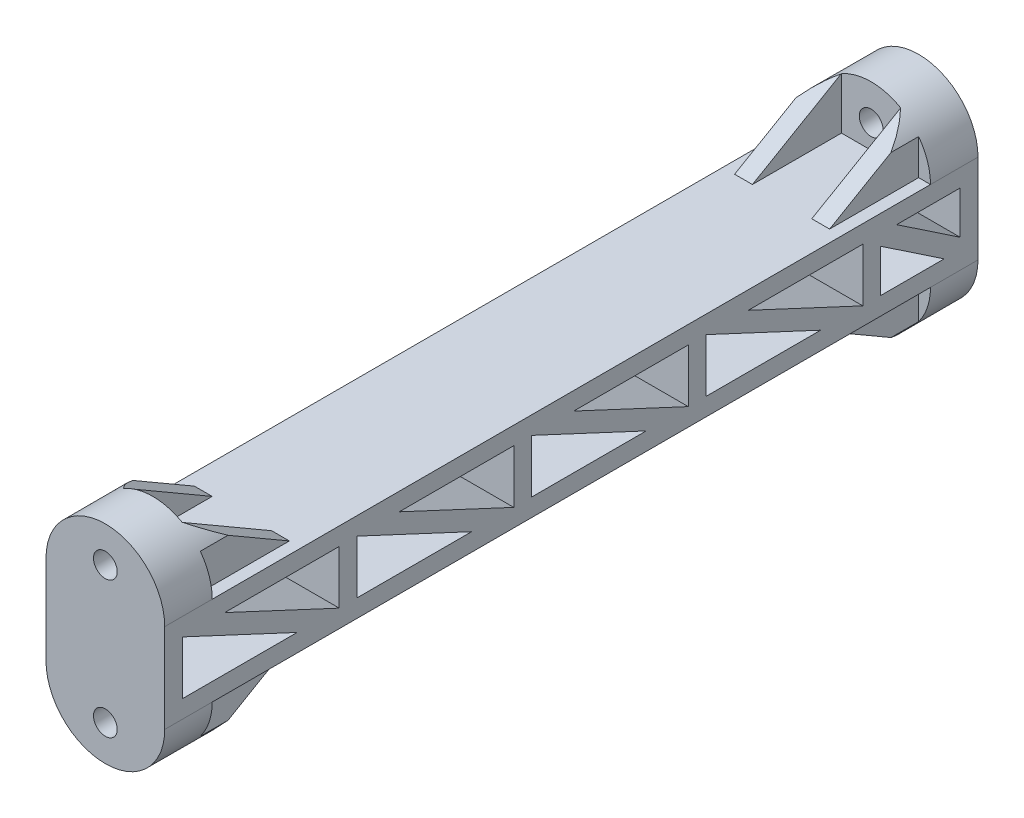
SolidWorks part; units mm, degrees
ref_plane "Front Plane" through (0, 0, 0) normal (0, 0, 1) x (1, 0, 0)
ref_plane "Top Plane" through (0, 0, 0) normal (0, 1, 0) x (1, 0, 0)
ref_plane "Right Plane" through (0, 0, 0) normal (1, 0, 0) x (0, 0, -1)
sketch "Sketch1" plane through (0, 0, 0) normal (0, 0, 1) x (1, 0, 0)
  line L0 (-10, -15) -> (10, -15) construction
  line L1 (10, 0) -> (-10, 0) construction
  line L2 (-10, -15) -> (10, -15)
  line L3 (10, 0) -> (-10, 0)
  circle A0 centre (0, -19) radius 2 construction
  arc A1 (-10, -15) -> (10, -15) centre (0, -15) ccw construction
  arc A2 (10, 0) -> (-10, 0) centre (0, 0) ccw construction
  circle A3 centre (0, 4) radius 2 construction
  circle A4 centre (0, -19) radius 2
  arc A5 (-10, -15) -> (10, -15) centre (0, -15) ccw
  arc A6 (10, 0) -> (-10, 0) centre (0, 0) ccw
  circle A7 centre (0, 4) radius 2
extrude "Boss-Extrude1" add sketch "Sketch1" against normal blind 8
sketch "Sketch2" plane through (-10, 0, 0) normal (-1, 0, 0) x (0, 0, 1)
  line L8 (67, -15) -> (67, -7.5)
  line L9 (67, -7.5) -> (54, -7.5)
  line L10 (54, -7.5) -> (54, 0)
  line L11 (54, 0) -> (0, 0)
  line L12 (0, 0) -> (-8, 0)
  line L13 (-8, 0) -> (-8, -15)
  line L14 (-8, -15) -> (0, -15)
  line L15 (0, -15) -> (67, -15)
  line L16 (67, -15) -> (67, -7.5)
  line L17 (67, -7.5) -> (54, -7.5)
  line L18 (54, -7.5) -> (54, 0)
  line L19 (54, 0) -> (0, 0)
  line L20 (0, 0) -> (-8, 0)
  line L21 (-8, 0) -> (-8, -15)
  line L22 (-8, -15) -> (0, -15)
  line L23 (0, -15) -> (67, -15)
  line L24 (54, 0) -> (54, -7.5)
  line L25 (54, -7.5) -> (67, -7.5)
  line L26 (67, -7.5) -> (67, -15)
  line L27 (67, -15) -> (121, -15)
  line L28 (121, -15) -> (129, -15)
  line L29 (129, -15) -> (129, 0)
  line L30 (129, 0) -> (121, 0)
  line L31 (121, 0) -> (54, 0)
  line L32 (54, 0) -> (54, -7.5)
  line L33 (54, -7.5) -> (67, -7.5)
  line L34 (67, -7.5) -> (67, -15)
  line L35 (67, -15) -> (121, -15)
  line L36 (121, -15) -> (129, -15)
  line L37 (129, -15) -> (129, 0)
  line L38 (129, 0) -> (121, 0)
  line L39 (121, 0) -> (54, 0)
  line M17 (67, -15) -> (67, -7.5)
  line M18 (67, -7.5) -> (54, -7.5)
  line M19 (54, -7.5) -> (54, 0)
  line M20 (54, 0) -> (0, 0)
  line M21 (0, 0) -> (-8, 0)
  line M22 (-8, 0) -> (-8, -15)
  line M23 (-8, -15) -> (0, -15)
  line M24 (0, -15) -> (67, -15)
  dimension "D1" = 0
  dimension "D2" = 0
extrude "Boss-Extrude2" add sketch "Sketch2" against normal blind 20 contours M24 M17 M18 M19 M20 M21 M22 M23
sketch "Sketch3" plane through (-10, 0, 0) normal (-1, 0, 0) x (0, 0, 1)
  line L8 (54, 0) -> (54, -7.5)
  line L9 (54, -7.5) -> (67, -7.5)
  line L10 (67, -7.5) -> (67, -15)
  line L11 (67, -15) -> (121, -15)
  line L12 (121, -15) -> (129, -15)
  line L13 (129, -15) -> (129, 0)
  line L14 (129, 0) -> (121, 0)
  line L15 (121, 0) -> (54, 0)
  line L16 (54, 0) -> (54, -7.5)
  line L17 (54, -7.5) -> (67, -7.5)
  line L18 (67, -7.5) -> (67, -15)
  line L19 (67, -15) -> (121, -15)
  line L20 (121, -15) -> (129, -15)
  line L21 (129, -15) -> (129, 0)
  line L22 (129, 0) -> (121, 0)
  line L23 (121, 0) -> (54, 0)
  dimension "D1" = 0
extrude "Boss-Extrude3" add sketch "Sketch3" against normal blind 20
sketch "Sketch4" plane through (0, 0, 121) normal (0, 0, -1) x (-1, 0, 0)
  line L1 (-10, 0) -> (10, 0)
  line L2 (-10, 0) -> (10, 0)
  line L3 (10, -15) -> (-10, -15)
  line L4 (10, -15) -> (-10, -15)
  circle A0 centre (0, -19) radius 2 construction
  arc A1 (10, 0) -> (-10, 0) centre (0, 0) ccw
  arc A2 (10, 0) -> (-10, 0) centre (0, 0) ccw
  arc A3 (-10, -15) -> (10, -15) centre (0, -15) ccw
  arc A4 (-10, -15) -> (10, -15) centre (0, -15) ccw
  circle A5 centre (0, 4) radius 2 construction
  circle A6 centre (0, -19) radius 2
  circle A7 centre (0, 4) radius 2
  dimension "D1" = 0
  dimension "D2" = 0
extrude "Boss-Extrude4" add sketch "Sketch4" against normal blind 8
sketch "Sketch6" plane through (10, 0, 0) normal (1, 0, 0) x (0, 0, -1)
  line L0 (0, -3) -> (-121, -3)
  line L1 (-121, -3) -> (-126, -3)
  line L2 (-126, -3) -> (-126, -12)
  line L3 (-126, -12) -> (-121, -12)
  line L4 (-121, -12) -> (0, -12)
  line L5 (0, -12) -> (5, -12)
  line L6 (5, -12) -> (5, -3)
  line L7 (5, -3) -> (0, -3)
  line L8 (0, -15) -> (8, -15)
  line L9 (8, -15) -> (8, 0)
  line L10 (8, 0) -> (0, 0)
  line L11 (0, 0) -> (-121, 0)
  line L12 (-121, 0) -> (-129, 0)
  line L13 (-129, 0) -> (-129, -15)
  line L14 (-129, -15) -> (-121, -15)
  line L15 (-121, -15) -> (0, -15)
  line L16 (0, -15) -> (8, -15)
  line L17 (8, -15) -> (8, 0)
  line L18 (8, 0) -> (0, 0)
  line L19 (0, 0) -> (-121, 0)
  line L20 (-121, 0) -> (-129, 0)
  line L21 (-129, 0) -> (-129, -15)
  line L22 (-129, -15) -> (-121, -15)
  line L23 (-121, -15) -> (0, -15)
  dimension "D1" = 0
  dimension "D2" = 3
extrude "Cut-Extrude1" cut sketch "Sketch6" against normal through all contours L0 L1 L2 L3 L4 L5 L6 L7
sketch "Sketch7" plane through (10, 0, 0) normal (1, 0, 0) x (0, 0, -1)
  line L0 (-126, -3) -> (-106.6994, -12)
  line L1 (-126, -3) -> (-118.9014, -3)
  line L2 (5, -3) -> (-126, -3) construction
  line L3 (-126, -12) -> (5, -12) construction
  line L4 (-99.6008, -12) -> (-106.6994, -12)
  line L5 (-126, -3) -> (-126, -12) construction
  line L6 (-118.9014, -3) -> (-99.6008, -12)
  line L7 (-124.7321, -0.2811) -> (-105.4316, -9.2811) construction
  line L8 (-99.6008, -12) -> (-99.6008, -3)
  line L9 (-96.6008, -12) -> (-96.6008, -3)
  line L10 (5, -3) -> (-126, -3)
  line L11 (-126, -12) -> (5, -12)
  line L12 (-96.6008, -3) -> (-77.3003, -12)
  line L13 (-89.5022, -3) -> (-70.2017, -12)
  line L14 (-95.333, -0.2811) -> (-76.0324, -9.2811) construction
  line L15 (-70.2017, -12) -> (-70.2017, -3)
  line L16 (-67.2017, -12) -> (-67.2017, -3)
  line L17 (-67.2017, -3) -> (-47.9011, -12)
  line L18 (-60.1031, -3) -> (-40.8025, -12)
  line L19 (-65.9338, -0.2811) -> (-46.6332, -9.2811) construction
  line L20 (-40.8025, -12) -> (-40.8025, -3)
  line L21 (-37.8025, -12) -> (-37.8025, -3)
  line L22 (-37.8025, -3) -> (-18.5019, -12)
  line L23 (-30.7039, -3) -> (-11.4033, -12)
  line L24 (-36.5346, -0.2811) -> (-17.2341, -9.2811) construction
  line L25 (-11.4033, -12) -> (-11.4033, -3)
  line L26 (-8.4033, -12) -> (-8.4033, -3)
  line L27 (-8.4033, -3) -> (5, -12)
  line L28 (-8.4033, -4.8068) -> (2.3092, -12)
  line L29 (-5.7126, -3) -> (5, -10.1932)
  line L30 (-9.2395, -4.2453) -> (4.1638, -13.2453) construction
  line L31 (5, -12) -> (5, -3) construction
  line L32 (5, -12) -> (5, -3)
  line L33 (-7.5671, -1.7547) -> (5.8362, -10.7547) construction
  point P39 (6.4204, -9.9124)
  point P41 (4.4741, -13.3294)
  point P42 (4.6457, -12)
  line M3 (-126, -3) -> (5, -3)
  line M4 (5, -3) -> (5, -12)
  line M5 (5, -12) -> (-126, -12)
  dimension "D1" = 65
  dimension "D2" = 3
  dimension "D3" = 3
  dimension "D4" = 65
  dimension "D6" = 3
  dimension "D7" = 65
  dimension "D9" = 3
  dimension "D10" = 65
  dimension "D12" = 3
  dimension "D13" = 1.5
  dimension "D5" = 3
  dimension "D8" = 3
  dimension "D11" = 3
  dimension "D14" = 1.5
extrude "Boss-Extrude5" add sketch "Sketch7" against normal up to surface (20 mm away) contours L26 L28 L27 M5 | L29 L10 L27 M4 | L11 L26 L25 M3 | L23 L22 L11 M3 | L11 L21 L10 L20 | L18 L10 L17 L11 | L11 L16 L15 M3 | L13 L12 L11 M3 | L9 L8 M5 M3 | L6 L0 M3 M5 up to face at (-10, -7.5, 60.5)
ref_plane "Plane1" through (5, 0, 0) normal (1, 0, 0) x (0, 0, -1)
sketch "Sketch9" plane through (5, 0, 0) normal (1, 0, 0) x (0, 0, -1)
  line L0 (0, -15) -> (0, -23.7021)
  line L1 (0, -15) -> (0, -25) construction
  line L2 (0, -23.7021) -> (-15, -15)
  line L3 (0, -15) -> (-121, -15) construction
  line L4 (0, -15) -> (-15, -15)
  point P5 (0, 0)
  dimension "D1" = 15
  dimension "D2" = 8.7021
extrude "Boss-Extrude6" add sketch "Sketch9" along normal blind 3
sketch "Sketch10" plane through (0, 0, 0) normal (0, 0, -1) x (-1, 0, 0)
  line L3 (-8, -21) -> (-8, -23.7021)
  line L4 (-8, -23.7021) -> (-5, -23.7021)
  line L5 (-5, -23.7021) -> (-5, -23.6603)
  line L6 (-8, -21) -> (-8, -23.7021)
  line L7 (-8, -23.7021) -> (-5, -23.7021)
  line L8 (-5, -23.7021) -> (-5, -23.6603)
  arc A1 (-8, -21) -> (-5, -23.6603) centre (0, -15) ccw
  arc A2 (-8, -21) -> (-5, -23.6603) centre (0, -15) ccw
  dimension "D1" = 0
extrude "Cut-Extrude2" cut sketch "Sketch10" against normal through all
ref_plane "Plane2" through (0, 0, 0) normal (1, 0, 0) x (0, 0, -1)
mirror "Mirror1" about plane through (0, 0, 0) normal (1, 0, 0) of "Cut-Extrude2", "Boss-Extrude6"
ref_plane "Plane3" through (0, 0, 60.5) normal (0, 0, -1) x (-1, 0, 0)
mirror "Mirror2" about plane through (0, 0, 60.5) normal (0, 0, -1) of "Cut-Extrude2", "Boss-Extrude6", "Mirror1"
ref_plane "Plane4" through (0, -7.5, 0) normal (0, 1, 0) x (1, 0, 0)
mirror "Mirror3" about plane through (0, -7.5, 0) normal (0, 1, 0) of "Mirror2", "Mirror1", "Cut-Extrude2", "Boss-Extrude6"
